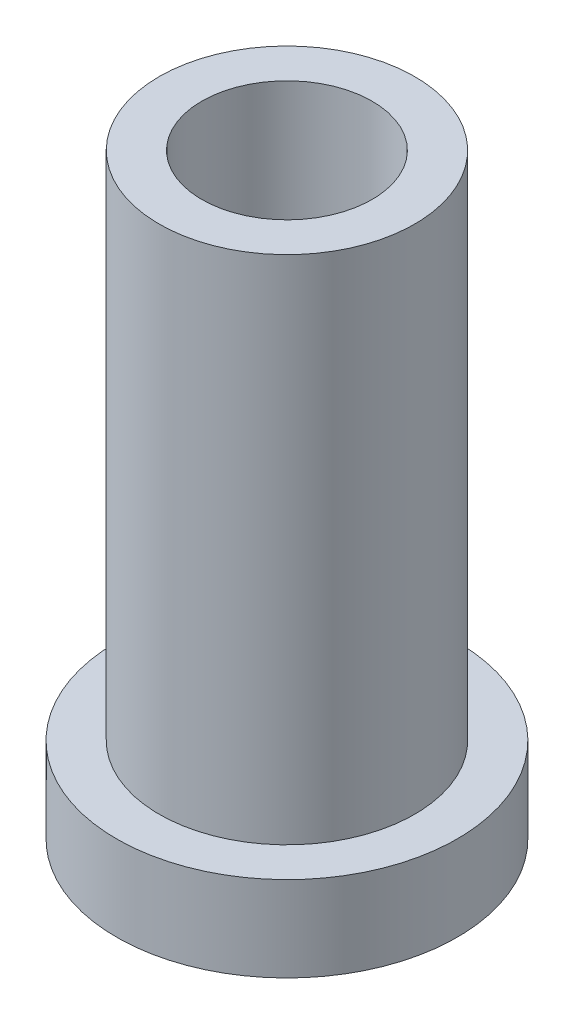
SolidWorks part; units mm, degrees
material "K110"
ref_plane "Front Plane" through (0, 0, 0) normal (0, 0, 1) x (1, 0, 0)
ref_plane "Top Plane" through (0, 0, 0) normal (0, 1, 0) x (1, 0, 0)
ref_plane "Right Plane" through (0, 0, 0) normal (1, 0, 0) x (0, 0, -1)
sketch "Sketch1" plane through (0, 0, 0) normal (0, 0, 1) x (1, 0, 0)
  line L0 (0, 0) -> (10, 0)
  line L1 (10, 0) -> (10, 5)
  line L2 (10, 5) -> (7.5, 5)
  line L3 (7.5, 5) -> (7.5, 35)
  line L4 (7.5, 35) -> (0, 35)
  line L5 (0, 35) -> (0, 0)
  line L6 (0, 40) -> (0, -5) construction
  point P9 (8.75, 5)
  dimension "D1" = 5
  dimension "D2" = 5
  dimension "D3" = 20
  dimension "D4" = 15
  dimension "D5" = 5
  dimension "D6" = 30
revolve "Revolve1" add sketch "Sketch1" angle 360 about L6
sketch "Sketch2" plane through (0, 35, 0) normal (0, 1, 0) x (1, 0, 0)
  circle A0 centre (0, 0) radius 5
  dimension "D1" = 10
extrude "Cut-Extrude1" cut sketch "Sketch2" against normal through all
